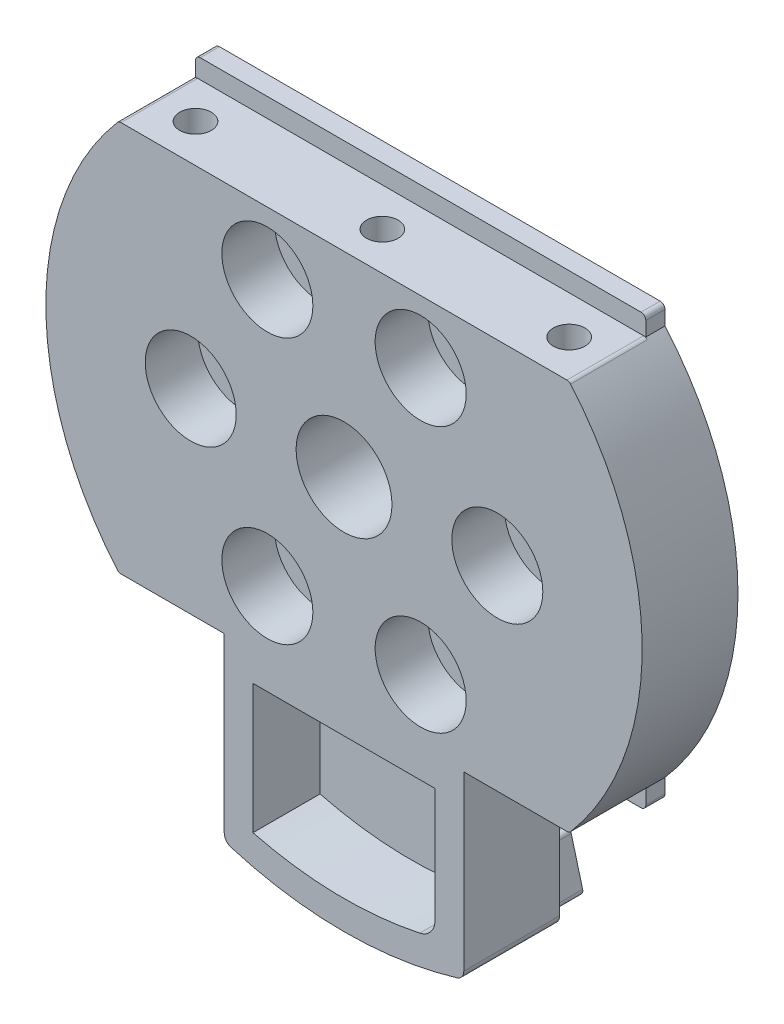
SolidWorks part; units mm, degrees
ref_plane "前视基准面" through (0, 0, 0) normal (0, 0, 1) x (1, 0, 0)
ref_plane "上视基准面" through (0, 0, 0) normal (0, 1, 0) x (1, 0, 0)
ref_plane "右视基准面" through (0, 0, 0) normal (1, 0, 0) x (0, 0, -1)
ref_plane "基准面1" through (0, 0, 0) normal (0, 0, -1) x (-1, 0, 0)
sketch "草图1" plane through (0, 0, 0) normal (0, 0, -1) x (-1, 0, 0)
  line L0 (12.5, -39.153) -> (23.5, -39.153)
  line L1 (23.5, -39.153) -> (23.5, -20.4)
  line L2 (23.5, 20.4) -> (-23.5, 20.4)
  line L3 (-23.5, -20.4) -> (-23.5, -39.153)
  line L4 (-23.5, -39.153) -> (-12.5, -39.153)
  arc A0 (-12.5, -39.153) -> (12.5, -39.153) centre (0, 0) ccw
  arc A1 (23.5, -20.4) -> (23.5, 20.4) centre (0, 0) ccw
  arc A2 (-23.5, 20.4) -> (-23.5, -20.4) centre (0, 0) ccw
extrude "凸台-拉伸1" add sketch "草图1" against normal blind 2
sketch "草图2" plane through (0, -39.153, 0) normal (0, -1, 0) x (1, 0, 0)
  line L0 (-12.5, 2) -> (-23.5, 2)
  line L1 (-23.5, 2) -> (-23.5, 0)
  line L2 (-23.5, 0) -> (-12.5, 0)
  line L3 (-12.5, 0) -> (-12.5, 2)
extrude "切除-拉伸1" cut sketch "草图2" against normal blind 16.753
sketch "草图3" plane through (0, -39.153, 0) normal (0, -1, 0) x (1, 0, 0)
  line L0 (12.5, 0) -> (23.5, 0)
  line L1 (23.5, 0) -> (23.5, 2)
  line L2 (23.5, 2) -> (12.5, 2)
  line L3 (12.5, 2) -> (12.5, 0)
extrude "切除-拉伸2" cut sketch "草图3" against normal blind 16.753
sketch "草图4" plane through (0, 0, 2) normal (0, 0, 1) x (1, 0, 0)
  line L0 (-12.5, -39.153) -> (-12.5, -20.4)
  line L1 (-12.5, -20.4) -> (-23.5, -20.4)
  line L2 (-23.5, 20.4) -> (23.5, 20.4)
  line L3 (23.5, -20.4) -> (12.5, -20.4)
  line L4 (12.5, -20.4) -> (12.5, -39.153)
  arc A0 (12.5, -39.153) -> (-12.5, -39.153) centre (0, 0) cw
  arc A1 (-23.5, -20.4) -> (-23.5, 20.4) centre (0, 0) cw
  arc A2 (23.5, 20.4) -> (23.5, -20.4) centre (0, 0) cw
extrude "凸台-拉伸2" add sketch "草图4" along normal blind 8
sketch "草图5" plane through (0, 20.4, 0) normal (0, 1, 0) x (-1, 0, 0)
  line L0 (-23.5, 2) -> (23.5, 2)
  line L1 (23.5, 2) -> (23.5, 0)
  line L2 (23.5, 0) -> (-23.5, 0)
  line L3 (-23.5, 0) -> (-23.5, 2)
extrude "凸台-拉伸3" add sketch "草图5" along normal blind 2
sketch "草图6" plane through (0, 0, 0) normal (0, 0, -1) x (-1, 0, 0)
  line L0 (9.1881, -34.2904) -> (10.6375, -39.6996)
  line L1 (-10.6375, -39.6996) -> (-9.1881, -34.2904)
  arc A0 (-9.1881, -34.2904) -> (9.1881, -34.2904) centre (0, 0) ccw
  arc A1 (10.6375, -39.6996) -> (-10.6375, -39.6996) centre (0, 0) cw
extrude "凸台-拉伸4" add sketch "草图6" along normal blind 4.4
sketch "草图7" plane through (0, 0, 10) normal (0, 0, 1) x (1, 0, 0)
  line L0 (9.5, -36.8966) -> (9.5, -23.4)
  line L1 (9.5, -23.4) -> (-9.5, -23.4)
  line L2 (-9.5, -23.4) -> (-9.5, -36.8966)
  arc A0 (-9.5, -36.8966) -> (9.5, -36.8966) centre (0, 0) ccw
extrude "切除-拉伸3" cut sketch "草图7" against normal blind 7
hole_wizard "Ø3.3 (3.3) 直径孔1" positions "草图9" profile "草图8" hole size "Ø3.3" standard "ANSI Metric"
sketch "草图9" plane through (0, 20.4, 0) normal (0, 1, 0) x (1, 0, 0)
  point P0 (-19.5, -6)
  point P1 (19.5, -6)
  point P2 (0, -6)
sketch "草图8" plane through (-19.5, 20.4, 6) normal (1, 0, 0) x (0, 0, 1)
  line L0 (0, 0) -> (0, 12.4914)
  line L1 (0, 12.4914) -> (1.65, 11.5)
  line L2 (1.65, 11.5) -> (1.65, 0)
  line L5 (1.65, 0) -> (0, 0)
  line L10 (0, 12.4914) -> (-1.65, 11.5) construction
  line L11 (0, -6.35) -> (0, 107.95) construction
  dimension "孔直径" = 3.3
  dimension "孔深度" = 11.5
  dimension "导头角度" = 118
hole_wizard "Ø3.3 (3.3) 直径孔2" positions "草图11" profile "草图10" hole size "Ø3.3" standard "ANSI Metric"
sketch "草图11" plane through (0, -20.4, 0) normal (0, -1, 0) x (1, 0, 0)
  point P0 (-19.5, -6)
  point P1 (-19.5, 6)
sketch "草图10" plane through (-19.5, -20.4, -6) normal (1, 0, 0) x (0, 0, -1)
  line L0 (0, 0) -> (0, 12.4914)
  line L1 (0, 12.4914) -> (1.65, 11.5)
  line L2 (1.65, 11.5) -> (1.65, 0)
  line L5 (1.65, 0) -> (0, 0)
  line L10 (0, 12.4914) -> (-1.65, 11.5) construction
  line L11 (0, -6.35) -> (0, 107.95) construction
  dimension "孔直径" = 3.3
  dimension "孔深度" = 11.5
  dimension "导头角度" = 118
hole_wizard "Ø10.0 (10) 直径孔1" positions "草图13" profile "草图12" hole size "Ø10.0" standard "ANSI Metric"
sketch "草图13" plane through (0, 0, 0) normal (0, 0, -1) x (-1, 0, 0)
  point P0 (0, 0)
sketch "草图12" plane through (0, 0, 0) normal (1, 0, 0) x (0, 1, 0)
  line L0 (0, 0) -> (0, 10)
  line L1 (0, 10) -> (5, 10)
  line L2 (5, 10) -> (5, 0)
  line L5 (5, 0) -> (0, 0)
  line L11 (0, -6.35) -> (0, 107.95) construction
  dimension "通孔孔直径" = 10
  dimension "通孔孔深度" = 10
hole_wizard "M5 六角头螺栓的柱形沉头孔1" positions "草图15" profile "草图14" counterbore size "M5" standard "ANSI Metric"
sketch "草图15" plane through (0, 0, 10) normal (0, 0, 1) x (1, 0, 0)
  point P0 (16, 0)
  point P1 (8, -13.8564)
  point P2 (-8, -13.8564)
  point P3 (-16, 0)
  point P4 (-8, 13.8564)
  point P5 (8, 13.8564)
sketch "草图14" plane through (16, 0, 10) normal (1, 0, 0) x (0, -1, 0)
  line L0 (0, 0) -> (0, 14.4)
  line L1 (0, 14.4) -> (2.75, 14.4)
  line L3 (2.75, 14.4) -> (2.75, 5.5)
  line L4 (2.75, 5.5) -> (4.75, 5.5)
  line L5 (4.75, 5.5) -> (4.75, 0)
  line L7 (4.75, 0) -> (0, 0)
  line L11 (0, -6.35) -> (0, 107.95) construction
  dimension "通孔孔直径" = 5.5
  dimension "通孔孔深度" = 14.4
  dimension "柱形沉头孔直径" = 9.5
  dimension "柱形沉头孔深度" = 5.5
fillet "圆角1" radius 0.5 12 edges at (-23.5, 20.4, 6) (23.5, -22.4, 1) (-10.6375, -39.6996, -2.2) (-9.1881, -34.2904, -2.2) (23.5, 22.4, 1) (10.6375, -39.6996, -2.2) (9.1881, -34.2904, -2.2) (-23.5, -20.4, 6) (-23.5, 22.4, 1) (-23.5, -22.4, 1) (23.5, -20.4, 6) (23.5, 20.4, 6)
fillet "圆角2" radius 1 2 edges at (-12.5, -39.153, 5) (12.5, -39.153, 5)
fillet "圆角4" radius 2 1 edges at (9.5, -36.8966, 6.5)
